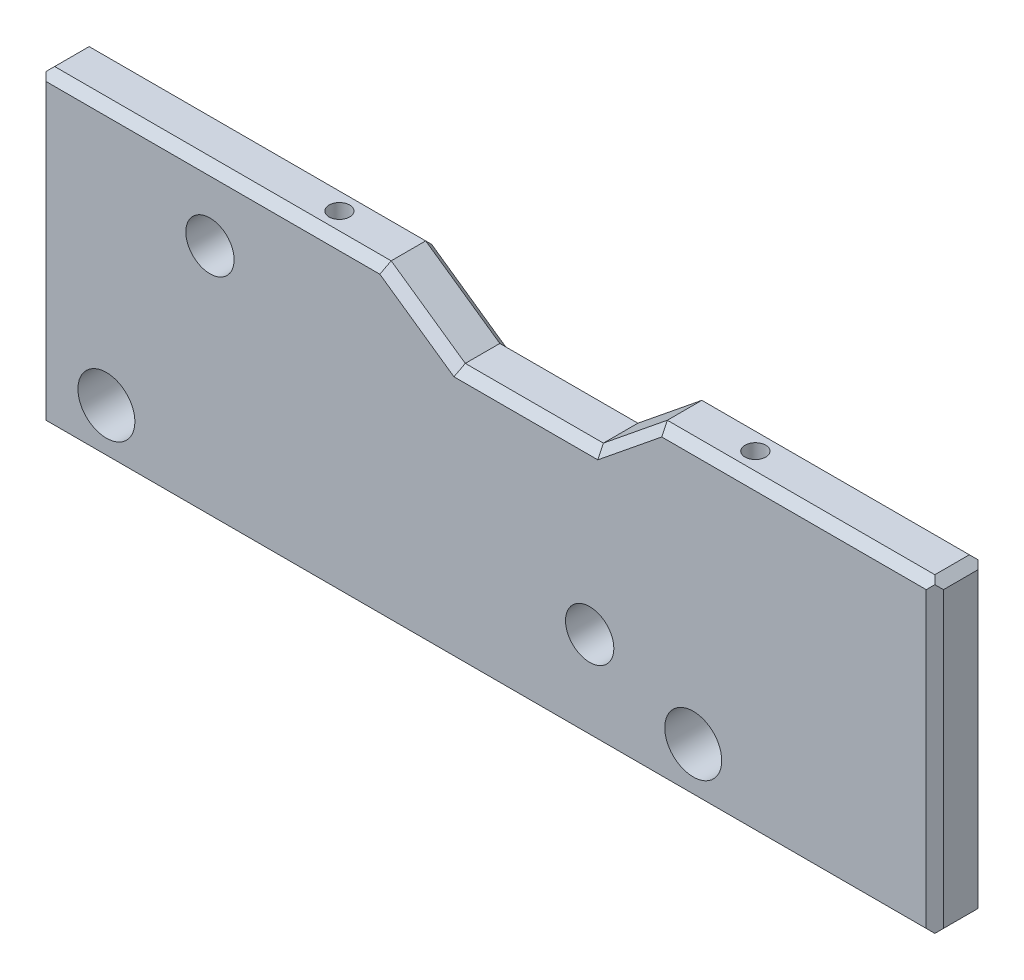
SolidWorks part; units mm, degrees
ref_plane "前视基准面" through (0, 0, 0) normal (0, 0, 1) x (1, 0, 0)
ref_plane "上视基准面" through (0, 0, 0) normal (0, 1, 0) x (1, 0, 0)
ref_plane "右视基准面" through (0, 0, 0) normal (1, 0, 0) x (0, 0, -1)
sketch "草图1" plane through (0, 0, 0) normal (0, 0, 1) x (1, 0, 0)
  line L0 (-8, 7) -> (-3.7059, 4)
  line L1 (-28, 7) -> (-8, 7)
  line L2 (-28, 7) -> (-28, -11)
  line L3 (-28, -11) -> (24, -11)
  line L4 (24, 7) -> (24, -11)
  line L7 (-3.7059, 4) -> (4.2941, 4)
  line L8 (4.2941, 4) -> (8, 7)
  line L9 (8, 7) -> (24, 7)
  circle A0 centre (-18, 3) radius 1.4
  circle A1 centre (4, -5.5) radius 1.4
  circle A3 centre (-24, -8) radius 1.65
  circle A4 centre (10, -8) radius 1.65
  circle A5 centre (4, -5.5) radius 2.5 construction
  circle A6 centre (10, -8) radius 2.5 construction
  point P0 (0, 0)
  dimension "D7" = 4
  dimension "D13" = 3
  dimension "D15" = 5
  dimension "D16" = 5
  dimension "D17" = 34
  dimension "D9" = 22
  dimension "D10" = 8.5
  dimension "D11" = 3.3
  dimension "D6" = 2.8
  dimension "D2" = 18
  dimension "D3" = 16
  dimension "D4" = 16
  dimension "D5" = 8
  dimension "D8" = 52
  dimension "D12" = 3
extrude "凸台-拉伸1" add sketch "草图1" along normal blind 3
sketch "草图2" plane through (0, -11, 0) normal (0, -1, 0) x (1, 0, 0)
  line L4 (-28, 0) -> (24, 0)
  line L5 (24, 0) -> (24, 3)
  line L6 (24, 3) -> (-28, 3)
  line L7 (-28, 3) -> (-28, 0)
  line L8 (-28, 0) -> (24, 0)
  line L9 (24, 0) -> (24, 3)
  line L10 (24, 3) -> (-28, 3)
  line L11 (-28, 3) -> (-28, 0)
  circle A0 centre (12.1, 1.5) radius 0.6
  circle A1 centre (-12, 1.5) radius 0.6
  dimension "D2" = 1.2
  dimension "D3" = 1.2
  dimension "D4" = 24.1
  dimension "D5" = 16
  dimension "D6" = 1.5
  dimension "D7" = 1.5
  dimension "D1" = 0
extrude "切除-拉伸1" cut sketch "草图2" against normal through all contours A0 | A1
chamfer "倒角2" distance 0.5 angle 45 8 edges at (-28, 7, 1.5) (-28, -2, 3) (-28, -11, 1.5) (-28, -2, 0) (24, -11, 1.5) (24, -2, 3) (24, 7, 1.5) (24, -2, 0)
chamfer "倒角3" distance 0.5 angle 45 12 edges at (15.75, 7, 0) (6.1471, 5.5, 0) (0.2941, 4, 0) (-5.8529, 5.5, 0) (-17.75, 7, 0) (-17.75, 7, 3) (-5.8529, 5.5, 3) (0.2941, 4, 3) (6.1471, 5.5, 3) (15.75, 7, 3) (-2, -11, 0) (-2, -11, 3)
